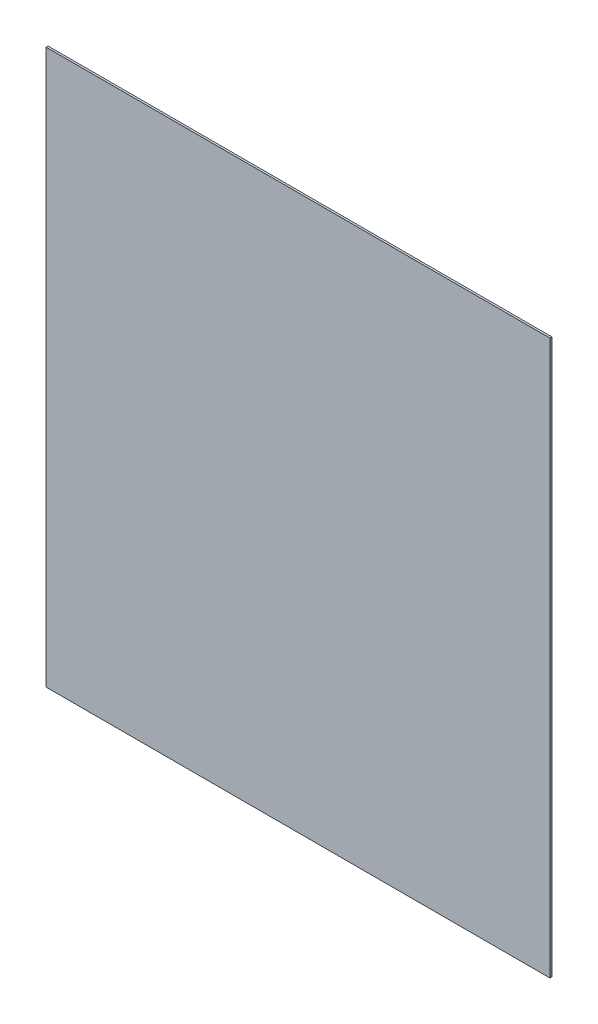
SolidWorks part; units mm, degrees
material "AISI 1045 Steel, cold drawn"
ref_plane "Front Plane" through (0, 0, 0) normal (0, 0, 1) x (1, 0, 0)
ref_plane "Top Plane" through (0, 0, 0) normal (0, 1, 0) x (1, 0, 0)
ref_plane "Right Plane" through (0, 0, 0) normal (1, 0, 0) x (0, 0, -1)
sketch "Sketch1" plane through (0, 0, 0) normal (0, 0, 1) x (1, 0, 0)
  line L1 (250, -275) -> (-250, -275)
  line L2 (250, -275) -> (250, 275)
  line L3 (250, 275) -> (-250, 275)
  line L4 (-250, -275) -> (-250, 275)
  line L5 (250, -275) -> (-250, 275) construction
  line L6 (250, 275) -> (-250, -275) construction
  point P0 (0, 0)
  dimension "D1" = 500
  dimension "D2" = 550
extrude "Boss-Extrude1" add sketch "Sketch1" along normal mid plane 2
